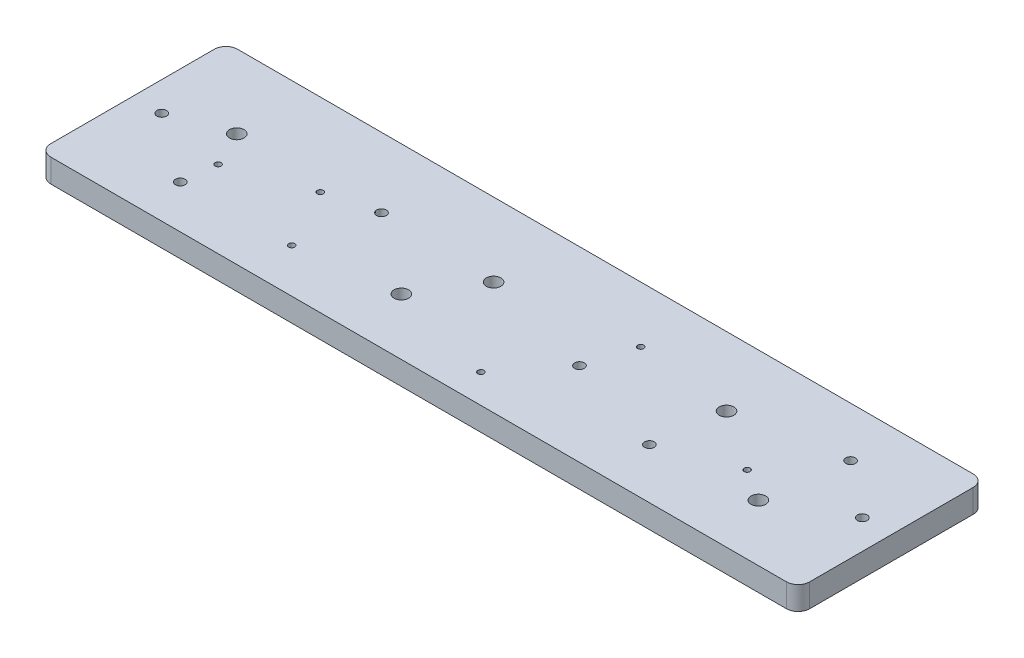
SolidWorks part; units mm, degrees
material "1060 Alloy"
ref_plane "Front Plane" through (0, 0, 0) normal (0, 0, 1) x (1, 0, 0)
ref_plane "Top Plane" through (0, 0, 0) normal (0, 1, 0) x (1, 0, 0)
ref_plane "Right Plane" through (0, 0, 0) normal (1, 0, 0) x (0, 0, -1)
sketch "Sketch1" plane through (0, 0, 0) normal (0, 1, 0) x (1, 0, 0)
  line L1 (0, 0) -> (650, 0)
  line L2 (0, 0) -> (0, 160)
  line L3 (0, 160) -> (650, 160)
  line L4 (650, 0) -> (650, 160)
  dimension "D1" = 160
  dimension "D2" = 650
extrude "Boss-Extrude1" add sketch "Sketch1" along normal blind 20 contours L3 L4 L1 L2
fillet "Fillet1" radius 10 4 edges at (0, 10, -160) (0, 10, 0) (650, 10, -160) (650, 10, 0)
sketch "Sketch4" plane through (0, 20, 0) normal (0, 1, 0) x (1, 0, 0)
  point P0 (72.3526, 96.8991)
  point P2 (261.6679, 48.5488)
  point P4 (487.7567, 100.9851)
  point P6 (567.4326, 48.5488)
  point P8 (292.3125, 96.8991)
hole_wizard "Ø12.5 (12.5) Diameter Hole1" positions "Sketch4" profile "Sketch3" hole size "Ø12.5" standard "DIN" end condition through all
sketch "Sketch3" plane through (72.3526, 20, -96.8991) normal (1, 0, 0) x (0, 0, 1)
  line L0 (0, 0) -> (0, 20)
  line L1 (0, 20) -> (6.25, 20)
  line L2 (6.25, 20) -> (6.25, 0)
  line L5 (6.25, 0) -> (0, 0)
  line L11 (0, -6.35) -> (0, 107.95) construction
  dimension "Thru Hole Dia." = 12.5
  dimension "Thru Hole Depth" = 20
sketch "Sketch7" plane through (0, 20, 0) normal (0, 1, 0) x (1, 0, 0)
  point P0 (192.8879, 100.3041)
  point P2 (83.9294, 36.972)
  point P4 (391.0561, 71.7025)
  point P6 (577.6474, 117.3288)
  point P8 (479.5848, 43.1009)
hole_wizard "Ø8.3 (8.3) Diameter Hole1" positions "Sketch7" profile "Sketch6" hole size "Ø8.3" standard "DIN" end condition through all
sketch "Sketch6" plane through (192.8879, 20, -100.3041) normal (1, 0, 0) x (0, 0, 1)
  line L0 (0, 0) -> (0, 20)
  line L1 (0, 20) -> (4.15, 20)
  line L2 (4.15, 20) -> (4.15, 0)
  line L5 (4.15, 0) -> (0, 0)
  line L11 (0, -6.35) -> (0, 107.95) construction
  dimension "Thru Hole Dia." = 8.3
  dimension "Thru Hole Depth" = 20
sketch "Sketch10" plane through (0, 20, 0) normal (0, 1, 0) x (1, 0, 0)
  point P0 (178.5871, 37.653)
  point P2 (151.3475, 89.4082)
  point P4 (353.6016, 24.7141)
  point P6 (403.3139, 111.8809)
  point P10 (540.1929, 66.2546)
  point P18 (87.0078, 66.2546)
hole_wizard "Ø5.2 (5.2) Diameter Hole1" positions "Sketch10" profile "Sketch9" hole size "Ø5.2" standard "DIN" end condition through all
sketch "Sketch9" plane through (178.5871, 20, -37.653) normal (1, 0, 0) x (0, 0, 1)
  line L0 (0, 0) -> (0, 20)
  line L1 (0, 20) -> (2.6, 20)
  line L2 (2.6, 20) -> (2.6, 0)
  line L5 (2.6, 0) -> (0, 0)
  line L11 (0, -6.35) -> (0, 107.95) construction
  dimension "Thru Hole Dia." = 5.2
  dimension "Thru Hole Depth" = 20
other "DeleteFace3" [suppressed]
sketch "Sketch11" plane through (0, 20, 0) normal (0, 1, 0) x (1, 0, 0)
  line L0 (0, 80) -> (25, 80) construction
  line L1 (0, 10) -> (0, 150) construction
  line L3 (650, 80) -> (625, 80) construction
  line L4 (650, 10) -> (650, 150) construction
  line L6 (10, 0) -> (640, 0) construction
  line L7 (25, 160) -> (25, 0) construction
  line L8 (10, 160) -> (640, 160) construction
  line L10 (625, 160) -> (625, 0) construction
  point P9 (25, 80)
  point P17 (625, 80)
  dimension "D1" = 25
  dimension "D2" = 25
hole_wizard "M8 Clearance Hole1" positions "Sketch11" profile "Sketch12" hole size "M8" standard "DIN" end condition through all
sketch "Sketch12" plane through (625, 20, -80) normal (1, 0, 0) x (0, 0, 1)
  line L0 (0, 0) -> (0, 20)
  line L1 (0, 20) -> (4.2, 20)
  line L2 (4.2, 20) -> (4.2, 0)
  line L5 (4.2, 0) -> (0, 0)
  line L11 (0, -6.35) -> (0, 107.95) construction
  dimension "Thru Hole Dia." = 8.4
  dimension "Thru Hole Depth" = 20
